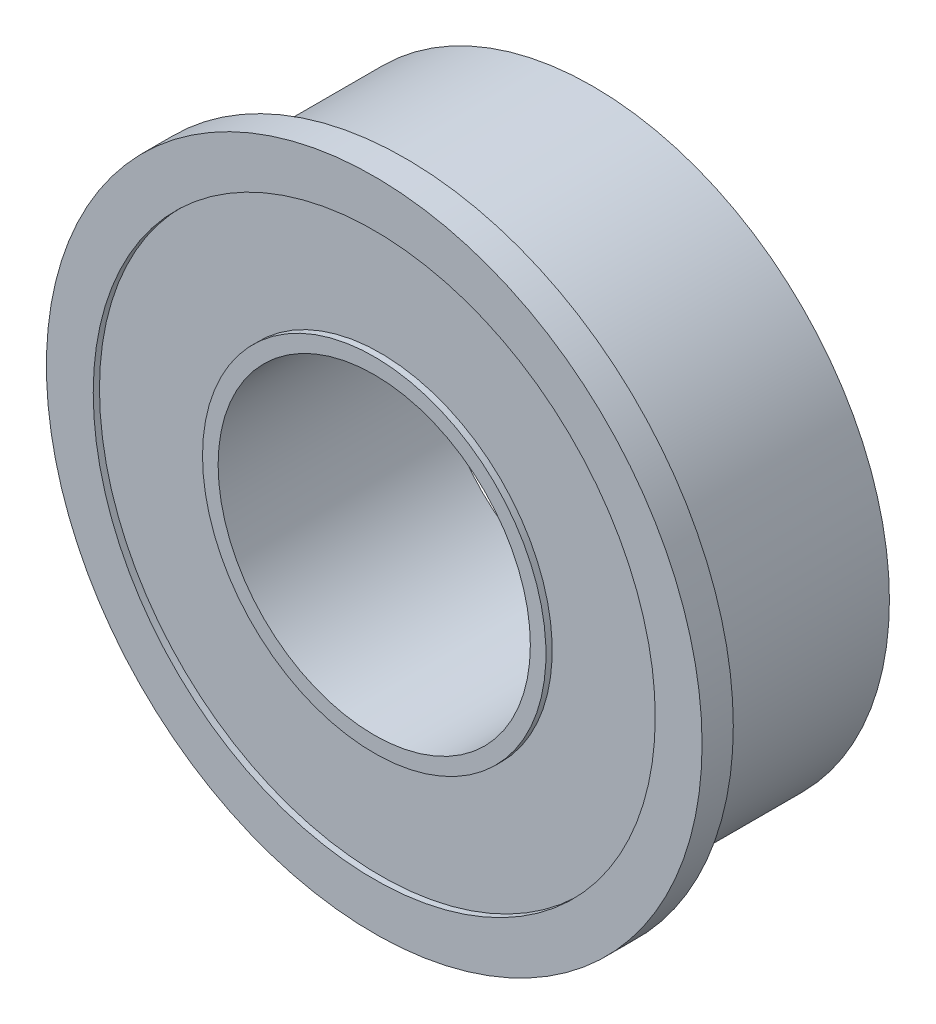
SolidWorks part; units mm, degrees
ref_plane "前视基准面" through (0, 0, 0) normal (0, 0, 1) x (1, 0, 0)
ref_plane "上视基准面" through (0, 0, 0) normal (0, 1, 0) x (1, 0, 0)
ref_plane "右视基准面" through (0, 0, 0) normal (1, 0, 0) x (0, 0, -1)
sketch "草图1" plane through (0, 0, 0) normal (0, 0, 1) x (1, 0, 0)
  circle A0 centre (0, 0) radius 9.5
  circle A1 centre (0, 0) radius 10.5
  dimension "D1" = 19
  dimension "D2" = 21
extrude "凸台-拉伸1" add sketch "草图1" along normal blind 1
sketch "草图2" plane through (0, 0, 1) normal (0, 0, 1) x (1, 0, 0)
  circle A0 centre (0, 0) radius 9.5
  circle A1 centre (0, 0) radius 5
  circle A3 centre (0, 0) radius 9.5 construction
  dimension "D2" = 10
extrude "凸台-拉伸2" add sketch "草图2" against normal blind 7
sketch "草图3" plane through (0, 0, -6) normal (0, 0, -1) x (-1, 0, 0)
  circle A0 centre (0, 0) radius 5.5
  circle A1 centre (0, 0) radius 9
  circle A2 centre (0, 0) radius 9.5 construction
  circle A3 centre (0, 0) radius 5 construction
  dimension "D1" = 0.5
  dimension "D2" = 0.5
extrude "切除-拉伸1" cut sketch "草图3" against normal blind 0.2
ref_plane "基准面1" through (0, 0, -2.5) normal (0, 0, -1) x (-1, 0, 0)
mirror "镜向1" about plane through (0, 0, -2.5) normal (0, 0, -1) of "切除-拉伸1"
